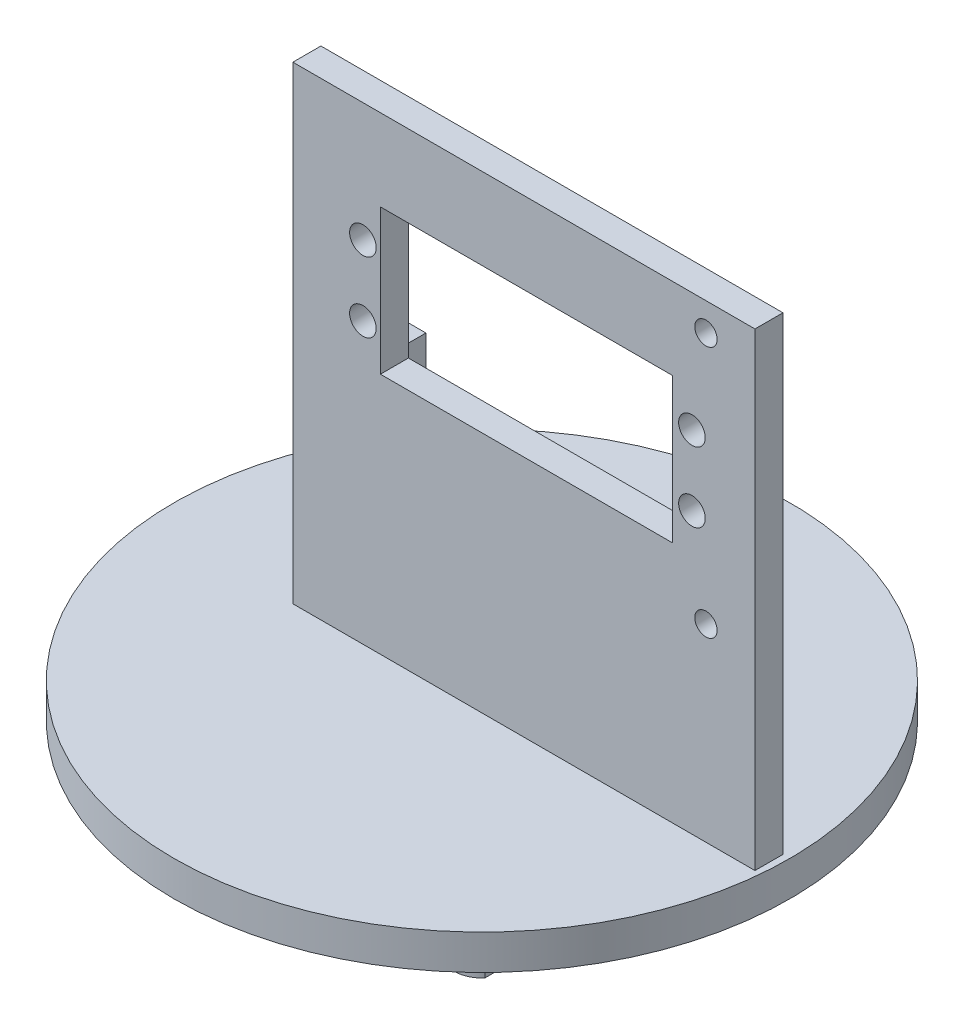
SolidWorks part; units mm, degrees
ref_plane "Front Plane" through (0, 0, 0) normal (0, 0, 1) x (1, 0, 0)
ref_plane "Top Plane" through (0, 0, 0) normal (0, 1, 0) x (1, 0, 0)
ref_plane "Right Plane" through (0, 0, 0) normal (1, 0, 0) x (0, 0, -1)
sketch "Yaw_platform_profile" plane through (0, 0, 0) normal (0, 1, 0) x (1, 0, 0)
  circle A0 centre (0, 0) radius 44
  dimension "D1" = 88
extrude "Yaw_platform" add sketch "Yaw_platform_profile" along normal blind 5 from offset 72
sketch "Printed_hollow_yaw_spindle_profile" plane through (0, 0, 0) normal (0, 1, 0) x (1, 0, 0)
  circle A0 centre (0, 0) radius 3.95
  circle A1 centre (0, 0) radius 1.75
  dimension "D1" = 7.9
  dimension "D2" = 3.5
extrude "Printed_hollow_yaw_spindle" add sketch "Printed_hollow_yaw_spindle_profile" along normal blind 29 from offset 43
sketch "Inner_race_load_shoulder_profile" plane through (0, 0, 0) normal (0, 1, 0) x (1, 0, 0)
  circle A0 centre (0, 0) radius 6
  circle A1 centre (0, 0) radius 1.75
  dimension "D1" = 12
  dimension "D2" = 3.5
extrude "Inner_race_load_shoulder" add sketch "Inner_race_load_shoulder_profile" along normal blind 2 from offset 70
sketch "D_flat_drive_key_profile" plane through (0, 0, 0) normal (0, 1, 0) x (1, 0, 0)
  line L1 (3, -5) -> (6, -5)
  line L2 (3, -5) -> (3, 5)
  line L3 (3, 5) -> (6, 5)
  line L4 (6, -5) -> (6, 5)
  dimension "D1" = 3
  dimension "D2" = 10
extrude "D_flat_on_spindle_end" cut sketch "D_flat_drive_key_profile" along normal blind 5 from offset 43
sketch "Shoulder_mount_plate_profile" plane through (0, 0, 0) normal (0, 0, 1) x (1, 0, 0)
  line L1 (-23, 76) -> (43, 76)
  line L2 (-23, 76) -> (-23, 144)
  line L3 (-23, 144) -> (43, 144)
  line L4 (43, 76) -> (43, 144)
  dimension "D1" = 66
  dimension "D2" = 68
extrude "Shoulder_mount_plate" add sketch "Shoulder_mount_plate_profile" along normal blind 4
sketch "MG996_body_window_profile" plane through (0, 0, 0) normal (0, 0, 1) x (1, 0, 0)
  line L1 (-10.5, 111.65) -> (31.2, 111.65)
  line L2 (-10.5, 111.65) -> (-10.5, 132.35)
  line L3 (-10.5, 132.35) -> (31.2, 132.35)
  line L4 (31.2, 111.65) -> (31.2, 132.35)
  dimension "D1" = 41.7
  dimension "D2" = 20.7
extrude "MG996_body_window" cut sketch "MG996_body_window_profile" along normal through all from offset 5
sketch "MG996_tab_mounts_profile" plane through (0, 0, 0) normal (0, 0, 1) x (1, 0, 0)
  circle A0 centre (-13, 117) radius 1.9
  circle A1 centre (-13, 127) radius 1.9
  circle A2 centre (34, 117) radius 1.9
  circle A3 centre (34, 127) radius 1.9
  dimension "D1" = 3.8
  dimension "D2" = 3.8
  dimension "D3" = 3.8
  dimension "D4" = 3.8
extrude "MG996_tab_mounts" cut sketch "MG996_tab_mounts_profile" along normal through all from offset 50
sketch "Passive_shoulder_standoffs_profile" plane through (0, 0, 0) normal (0, 0, 1) x (1, 0, 0)
  circle A0 centre (36, 104) radius 1.6
  circle A1 centre (36, 140) radius 1.6
  dimension "D1" = 3.2
  dimension "D2" = 3.2
extrude "Passive_shoulder_standoffs" cut sketch "Passive_shoulder_standoffs_profile" along normal through all from offset 50
sketch "Upright_rib_profile" plane through (0, 0, 0) normal (0, 0, 1) x (1, 0, 0)
  line L1 (-23, 77) -> (-16, 77)
  line L2 (-23, 77) -> (-23, 108)
  line L3 (-23, 108) -> (-16, 108)
  line L4 (-16, 77) -> (-16, 108)
  dimension "D1" = 7
  dimension "D2" = 31
extrude "Upright_rib" add sketch "Upright_rib_profile" along normal blind 12 from offset 8
